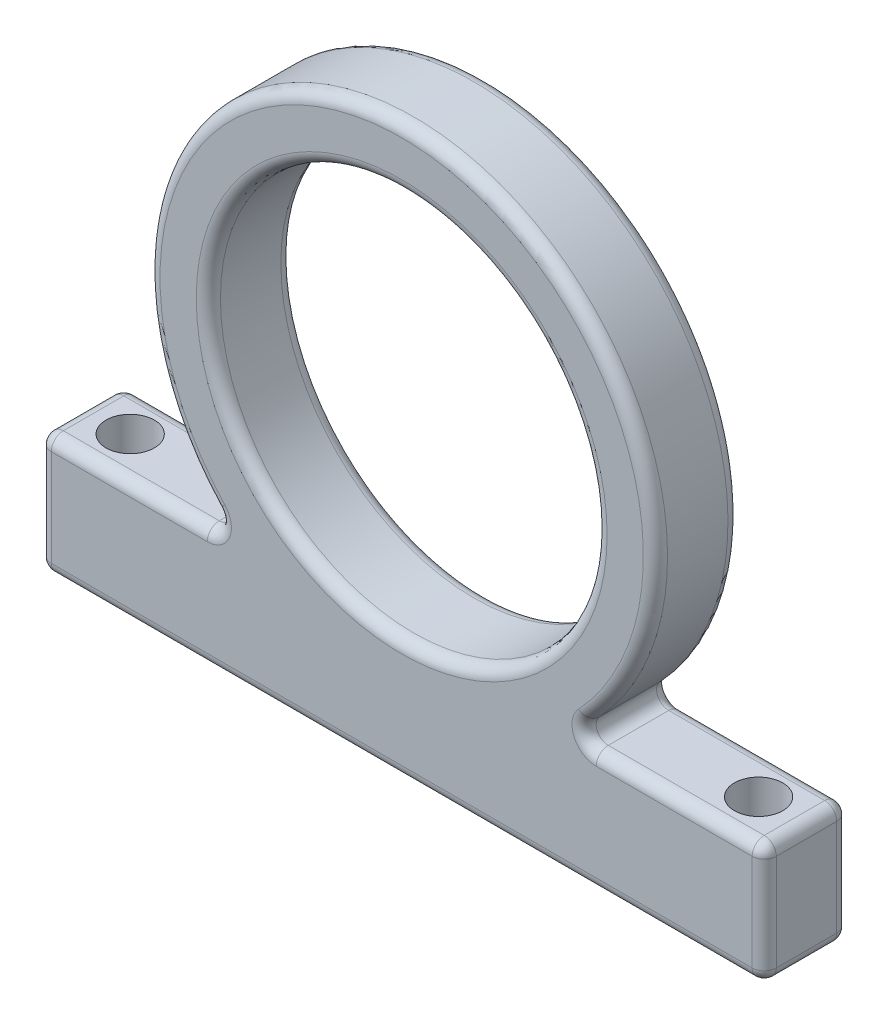
SolidWorks part; units mm, degrees
ref_plane "Front Plane" through (0, 0, 0) normal (0, 0, 1) x (1, 0, 0)
ref_plane "Top Plane" through (0, 0, 0) normal (0, 1, 0) x (1, 0, 0)
ref_plane "Right Plane" through (0, 0, 0) normal (1, 0, 0) x (0, 0, -1)
sketch "Sketch2" plane through (0, 0, 0) normal (0, 0, 1) x (1, 0, 0)
  line L6 (30, -16) -> (30, -26)
  line L7 (30, -26) -> (-30, -26)
  line L8 (-30, -26) -> (-30, -16)
  line L10 (13.6015, -16) -> (30, -16)
  line L11 (-13.6015, -16) -> (-30, -16)
  circle A1 centre (0, 0) radius 16
  arc A3 (-13.6015, -16) -> (13.6015, -16) centre (0, 0) cw
  dimension "D1" = 32
  dimension "D4" = 10
  dimension "D6" = 10
extrude "Boss-Extrude1" add sketch "Sketch2" along normal blind 7
fillet "Fillet2" radius 1 10 edges at (21.8007, -16, 7) (-21.8007, -16, 7) (21.8007, -16, 0) (-21.8007, -16, 0) (16, 0, 7) (0, 21, 7) (0, 21, 0) (16, 0, 0) (13.6015, -16, 3.5) (-13.6015, -16, 3.5)
fillet "Fillet3" radius 1 14 edges at (-30, -16.2929, 0.2929) (-30, -16.2929, 6.7071) (30, -16.2929, 0.2929) (30, -16.2929, 6.7071) (-30, -26, 3.5) (-30, -16, 3.5) (-30, -21.5, 0) (-30, -21.5, 7) (30, -16, 3.5) (30, -21.5, 0) (30, -26, 3.5) (0, -26, 0) (0, -26, 7) (30, -21.5, 7)
sketch "Sketch3" plane through (0, -16, 0) normal (0, 1, 0) x (1, 0, 0)
  line L0 (-29, -1) -> (-29, -6) construction
  line L1 (29, -6) -> (29, -1) construction
  circle A0 centre (-26, -3.4677) radius 2
  circle A1 centre (26, -3.4677) radius 2
  dimension "D1" = 4
  dimension "D2" = 4
  dimension "D3" = 3
  dimension "D4" = 3
  dimension "D5" = 52
extrude "Cut-Extrude1" cut sketch "Sketch3" against normal blind 100
